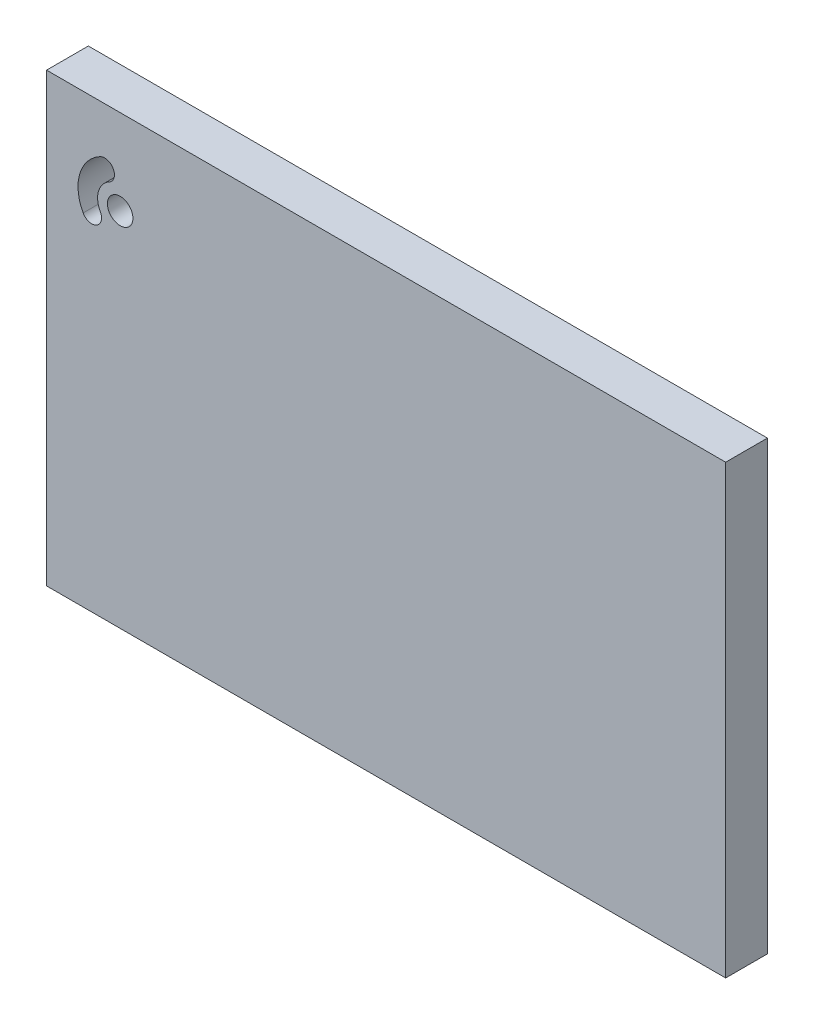
SolidWorks part; units mm, degrees
ref_plane "Спереди" through (0, 0, 0) normal (0, 0, 1) x (1, 0, 0)
ref_plane "Сверху" through (0, 0, 0) normal (0, 1, 0) x (1, 0, 0)
ref_plane "Справа" through (0, 0, 0) normal (1, 0, 0) x (0, 0, -1)
sketch "Эскиз1_fr" plane through (0, 0, 0) normal (0, 0, 1) x (1, 0, 0)
  line L1 (-39.7207, 48.8394) -> (122.8713, 48.8394)
  line L2 (-39.7207, 48.8394) -> (-39.7207, -58.1127)
  line L3 (-39.7207, -58.1127) -> (122.8713, -58.1127)
  line L4 (122.8713, 48.8394) -> (122.8713, -58.1127)
  arc A0 (-28.9018, 24.7288) -> (-25.8107, 35.2386) centre (-22.1014, 28.4381) cw construction
  arc A1 (-26.9341, 37.2982) -> (-30.9614, 23.6054) centre (-22.1014, 28.4381) ccw
  arc A2 (-24.6873, 33.179) -> (-26.8422, 25.8522) centre (-22.1014, 28.4381) ccw
  arc A3 (-24.6873, 33.179) -> (-26.9341, 37.2982) centre (-25.8107, 35.2386) ccw
  arc A4 (-30.9614, 23.6054) -> (-26.8422, 25.8522) centre (-28.9018, 24.7288) ccw
  circle A5 centre (-22.1014, 28.4381) radius 3.0529
  point P7 (-29.5329, 30.6239)
extrude "Бобышка-Вытянуть1" add sketch "Эскиз1_fr" along normal blind 10
